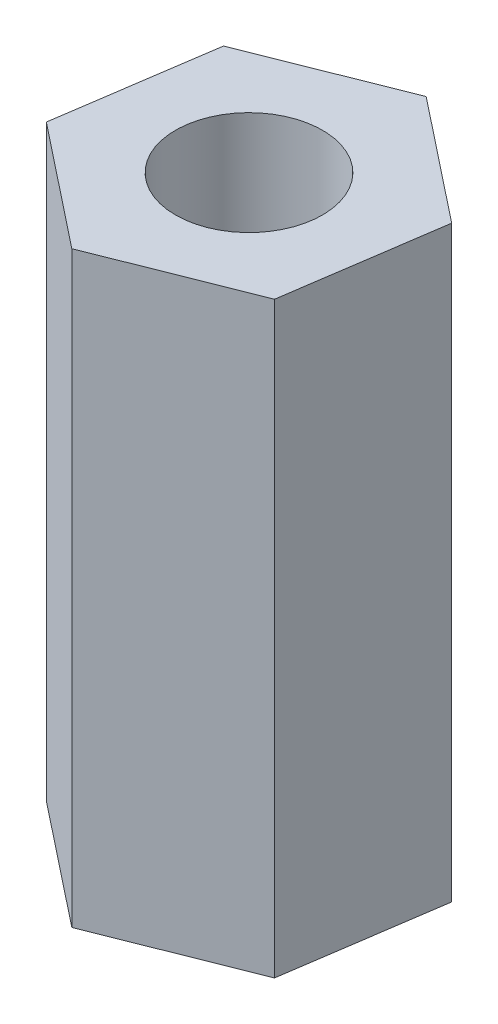
SolidWorks part; units mm, degrees
ref_plane "Alzado" through (0, 0, 0) normal (0, 0, 1) x (1, 0, 0)
ref_plane "Planta" through (0, 0, 0) normal (0, 1, 0) x (1, 0, 0)
ref_plane "Vista lateral" through (0, 0, 0) normal (1, 0, 0) x (0, 0, -1)
sketch "Croquis base" plane through (0, 0, 0) normal (0, 1, 0) x (1, 0, 0)
  line L1 (2.0823, -1.6485) -> (2.4688, 0.9791)
  line L2 (2.4688, 0.9791) -> (0.3865, 2.6275)
  line L3 (0.3865, 2.6275) -> (-2.0823, 1.6485)
  line L4 (-2.0823, 1.6485) -> (-2.4688, -0.9791)
  line L5 (-2.4688, -0.9791) -> (-0.3865, -2.6275)
  line L6 (-0.3865, -2.6275) -> (2.0823, -1.6485)
  circle A0 centre (0, 0) radius 2.3 construction
  dimension "D1" = 4.6
extrude "Saliente-Extruir1" add sketch "Croquis base" along normal blind 10
sketch "Croquis cara" plane through (0, 10, 0) normal (0, 1, 0) x (1, 0, 0)
  circle A0 centre (0, 0) radius 1.25
  dimension "D1" = 2.5
extrude "Cortar-Extruir1" cut sketch "Croquis cara" against normal through all
